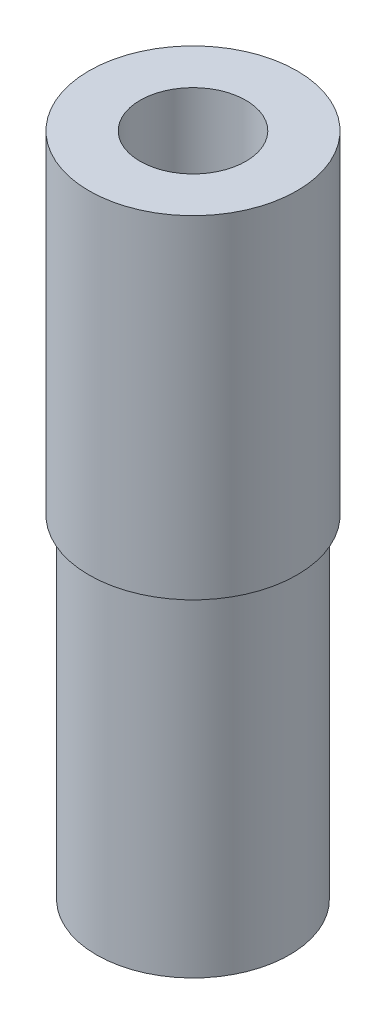
SolidWorks part; units mm, degrees
ref_plane "Front Plane" through (0, 0, 0) normal (0, 0, 1) x (1, 0, 0)
ref_plane "Top Plane" through (0, 0, 0) normal (0, 1, 0) x (1, 0, 0)
ref_plane "Right Plane" through (0, 0, 0) normal (1, 0, 0) x (0, 0, -1)
sketch "Sketch1" plane through (0, 0, 0) normal (0, 0, 1) x (1, 0, 0)
  line L1 (0, 0) -> (3.683, 0)
  line L4 (3.683, 0) -> (3.683, 12.7)
  line L5 (3.683, 12.7) -> (3.9688, 12.7)
  line L6 (0, 0) -> (0, 25.4)
  line L7 (0, 25.4) -> (3.9688, 25.4)
  line L8 (3.9688, 12.7) -> (3.9688, 25.4)
  dimension "D1" = 25.4
  dimension "D2" = 12.7
  dimension "D3" = 3.683
  dimension "D4" = 3.9688
revolve "Revolve1" add sketch "Sketch1" angle 360 about L6
hole_wizard "#10-32 Tapped Hole1" positions "Sketch3" profile "Sketch4" tap size "#10-32" standard "ANSI Inch"
sketch "Sketch3" plane through (0, 25.4, 0) normal (0, 1, 0) x (1, 0, 0)
  point P0 (0, 0)
sketch "Sketch4" plane through (0, 25.4, 0) normal (1, 0, 0) x (0, 0, 1)
  line L0 (0, 0) -> (0, 13.9133)
  line L1 (0, 13.9133) -> (2.0193, 12.7)
  line L2 (2.0193, 12.7) -> (2.0193, 0)
  line L5 (2.0193, 0) -> (0, 0)
  line L10 (0, 13.9133) -> (-2.0193, 12.7) construction
  line L11 (0, -6.35) -> (0, 107.95) construction
  dimension "Tap Drill Dia." = 4.0386
  dimension "Tap Drill Depth" = 12.7
  dimension "Drill Angle" = 118
cosmetic thread "Hole Thread1" parameters "D1"=10.16, "D2"=4.826
hole_wizard "#10-24 Tapped Hole1" positions "Sketch6" profile "Sketch5" tap size "#10-24" standard "ANSI Inch"
sketch "Sketch6" plane through (0, 0, 0) normal (0, -1, 0) x (-1, 0, 0)
  point P0 (0, 0)
sketch "Sketch5" plane through (0, 0, 0) normal (1, 0, 0) x (0, 0, -1)
  line L0 (0, 0) -> (0, 16.3808)
  line L1 (0, 16.3808) -> (1.8986, 15.24)
  line L2 (1.8986, 15.24) -> (1.8986, 0)
  line L5 (1.8986, 0) -> (0, 0)
  line L10 (0, 16.3808) -> (-1.8987, 15.24) construction
  line L11 (0, -6.35) -> (0, 107.95) construction
  dimension "Tap Drill Dia." = 3.7973
  dimension "Tap Drill Depth" = 15.24
  dimension "Drill Angle" = 118
cosmetic thread "Hole Thread2" parameters "D1"=12.7, "D2"=4.826
